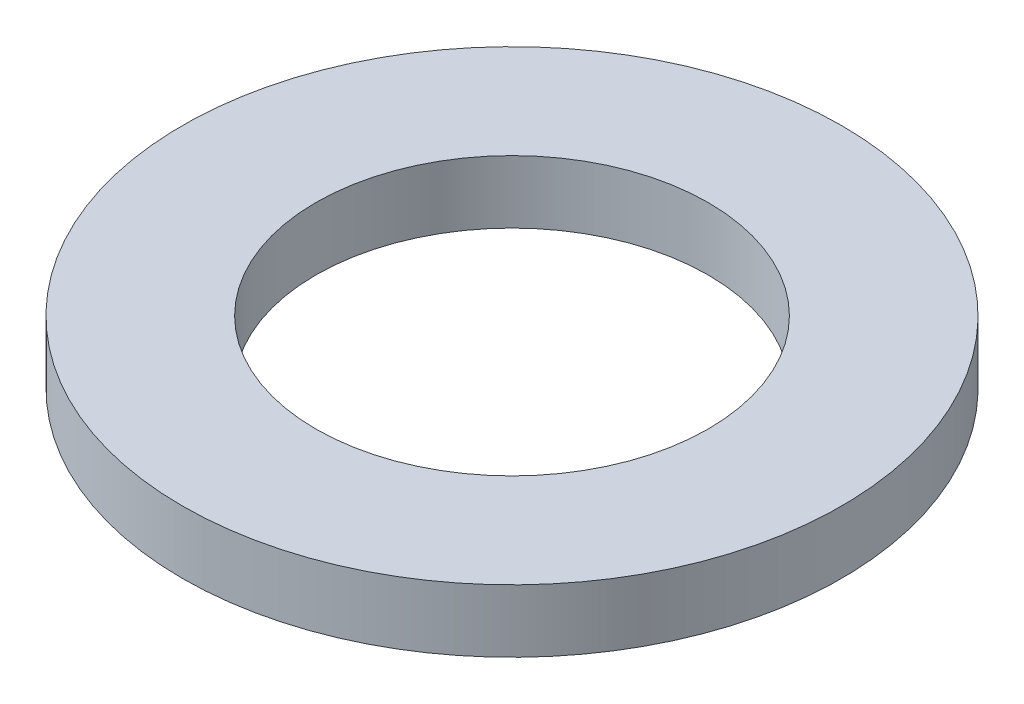
SolidWorks part; units mm, degrees
material "AISI 304"
ref_plane "前视基准面" through (0, 0, 0) normal (0, 0, 1) x (1, 0, 0)
ref_plane "上视基准面" through (0, 0, 0) normal (0, 1, 0) x (1, 0, 0)
ref_plane "右视基准面" through (0, 0, 0) normal (1, 0, 0) x (0, 0, -1)
other "Configuration Table"
sketch "草图1" plane through (0, 0, 0) normal (0, 1, 0) x (1, 0, 0)
  circle A0 centre (0, 0) radius 21
  circle A1 centre (0, 0) radius 12.5
  dimension "D1" = 25
  dimension "D2" = 42
extrude "凸台-拉伸1" add sketch "草图1" along normal blind 4
